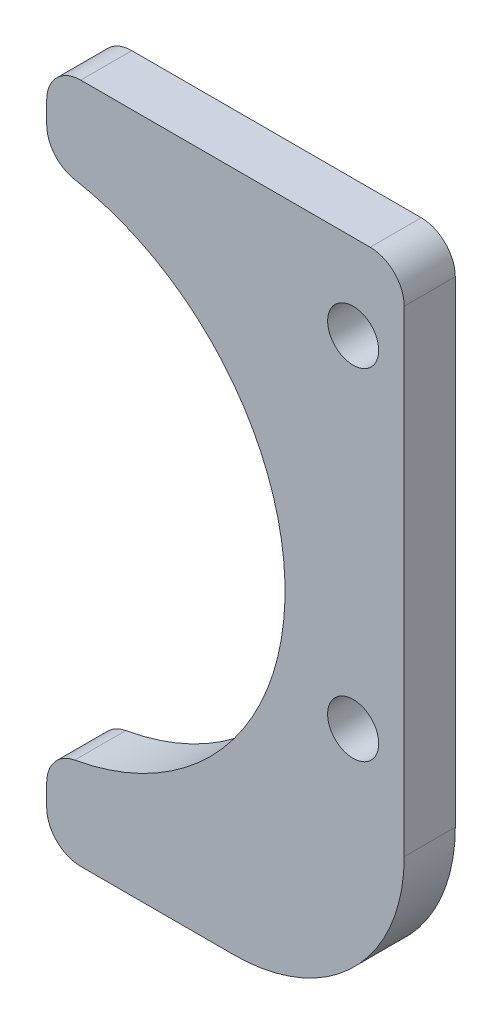
SolidWorks part; units mm, degrees
material "Hexcel AS4C (3000 丝)"
ref_plane "前视基准面" through (0, 0, 0) normal (0, 0, 1) x (1, 0, 0)
ref_plane "上视基准面" through (0, 0, 0) normal (0, 1, 0) x (1, 0, 0)
ref_plane "右视基准面" through (0, 0, 0) normal (1, 0, 0) x (0, 0, -1)
sketch "草图1" plane through (0, 0, 0) normal (0, 0, 1) x (1, 0, 0)
  line L0 (-22, 0) -> (22, 0) construction
  line L1 (-22, 20) -> (22, 20) construction
  line L2 (-22, 20) -> (-22, -20) construction
  line L3 (-22, -20) -> (22, -20) construction
  line L4 (22, 20) -> (22, -20)
  line L5 (-22, 20) -> (22, -20) construction
  line L6 (-22, -20) -> (22, 20) construction
  line L7 (1, 20) -> (1, 14.9666)
  line L8 (0, 0) -> (0, 20) construction
  line L9 (1, 0.9091) -> (1, -0.9091)
  line L10 (1, -14.9666) -> (1, -20)
  line L11 (1, 20) -> (22, 20)
  line L12 (1, -20) -> (22, -20)
  arc A0 (1, -14.9666) -> (1, 14.9666) centre (0, 0) ccw construction
  arc A1 (1, -14.9666) -> (1, 14.9666) centre (0, 0) ccw
  dimension "D1" = 30
  dimension "D2" = 22
  dimension "D3" = 1
  dimension "D4" = 40
extrude "凸台-拉伸1" add sketch "草图1" along normal blind 3 contours L11 L4 L12 L10 A1 L7
sketch "草图2" plane through (0, 0, 3) normal (0, 0, 1) x (1, 0, 0)
  line L0 (19, 20) -> (19, -20) construction
  line L1 (1, 20) -> (22, 20) construction
  line L2 (1, -20) -> (22, -20) construction
  line L3 (22, 20) -> (22, -20) construction
  circle A0 centre (19, 15) radius 1.5
  circle A1 centre (19, -5) radius 1.5
  dimension "D1" = 3
  dimension "D2" = 5
  dimension "D4" = 20
  dimension "D3" = 3
extrude "切除-拉伸1" cut sketch "草图2" against normal through all
fillet "圆角1" radius 10 1 edges at (22, -20, 1.5)
fillet "圆角2" radius 2 5 edges at (1, -20, 1.5) (1, -14.9666, 1.5) (1, 14.9666, 1.5) (1, 20, 1.5) (22, 20, 1.5)
